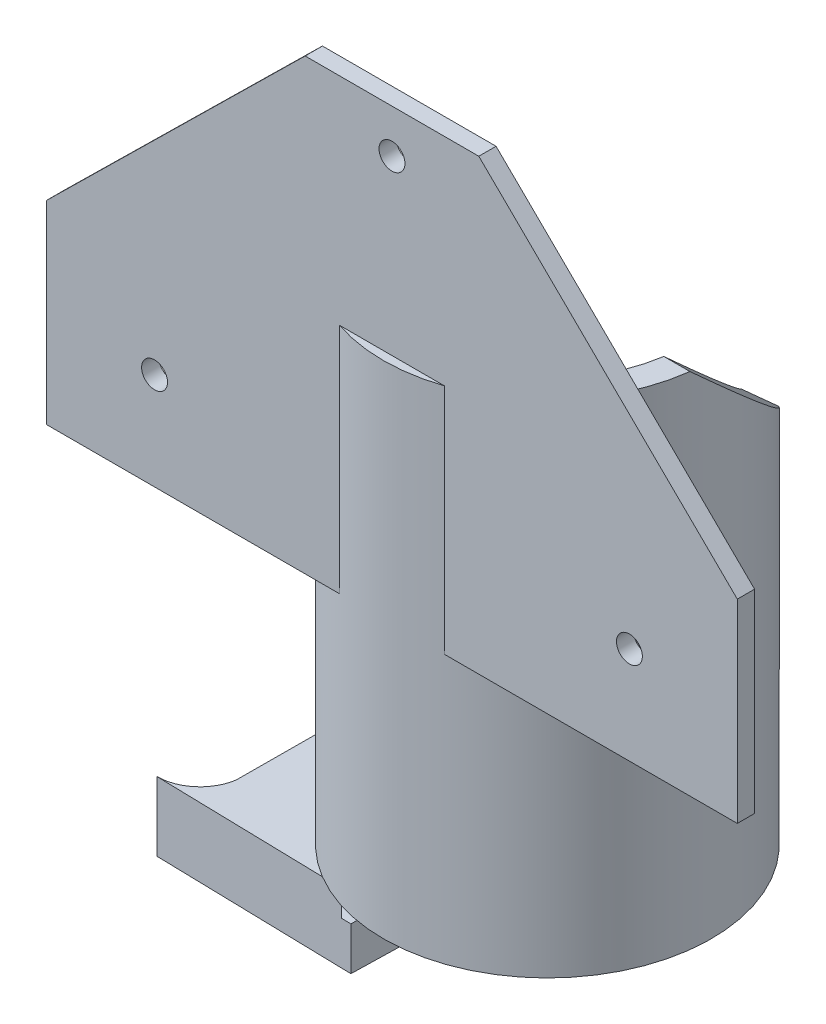
SolidWorks part; units mm, degrees
ref_plane "Front Plane" through (0, 0, 0) normal (0, 0, 1) x (1, 0, 0)
ref_plane "Top Plane" through (0, 0, 0) normal (0, 1, 0) x (1, 0, 0)
ref_plane "Right Plane" through (0, 0, 0) normal (1, 0, 0) x (0, 0, -1)
sketch "Sketch1" plane through (0, 0, 0) normal (0, 1, 0) x (1, 0, 0)
  circle A0 centre (0, 0) radius 19
  dimension "D1" = 38
extrude "Boss-Extrude1" add sketch "Sketch1" along normal blind 53 and the other way blind 5
sketch "Sketch2" plane through (0, 53, 0) normal (0, 1, 0) x (1, 0, 0)
  circle A0 centre (0, 0) radius 16
extrude "Cut-Extrude1" cut sketch "Sketch2" against normal blind 22
sketch "Sketch3" plane through (0, 53, 0) normal (0, 1, 0) x (1, 0, 0)
  line L1 (-12.5, 6) -> (12.5, 6)
  line L2 (-12.5, 6) -> (-12.5, 26)
  line L3 (-12.5, 26) -> (12.5, 26)
  line L4 (12.5, 6) -> (12.5, 26)
  line L5 (-12.5, 6) -> (12.5, 26) construction
  line L6 (-12.5, 26) -> (12.5, 6) construction
  circle A0 centre (0, 0) radius 16 construction
  point P0 (0, 16)
extrude "Cut-Extrude2" cut sketch "Sketch3" against normal blind 108
sketch "Sketch7" plane through (0, 0, 0) normal (1, 0, 0) x (0, 0, -1)
  line L0 (14.3091, 53) -> (14.3091, 38)
  line L1 (14.3091, -5) -> (14.3091, 53) construction
  line L2 (14.3091, 38) -> (-2.3455, 53)
  line L3 (14.3091, 53) -> (-19, 53) construction
  line L4 (-2.3455, 53) -> (14.3091, 53)
extrude "Cut-Extrude3" cut sketch "Sketch7" against normal blind 108 and the other way blind 108
ref_plane "Plane1" through (0, 0, 18) normal (0, 0, 1) x (1, 0, 0)
sketch "Sketch8" plane through (0, 0, 18) normal (0, 0, 1) x (1, 0, 0)
  line L1 (10.0571, 78.0232) -> (40, 48.5711)
  line L2 (40, 48.5711) -> (40, 26.0711)
  line L3 (40, 26.0711) -> (0, 26.0711)
  line L5 (0, -16.3611) -> (0, 16.3611) construction
  line L7 (-40, 26.0711) -> (0, 26.0711)
  line L8 (-40, 48.5711) -> (-40, 26.0711)
  line L9 (-10.0571, 78.0232) -> (-40, 48.5711)
  line L11 (-10.0571, 78.0232) -> (10.0571, 78.0232)
extrude "Boss-Extrude2" add sketch "Sketch8" against normal blind 2
sketch "Sketch10" plane through (0, 0, 16) normal (0, 0, -1) x (-1, 0, 0)
  line L0 (0, 53) -> (0, 73) construction
  line L1 (-19, 37.3211) -> (-27.5, 37.3211) construction
  line L2 (-19, 50.8876) -> (-19, -5) construction
  line L3 (19, 37.3211) -> (27.5, 37.3211) construction
  line L4 (19, -5) -> (19, 50.8876) construction
  circle A0 centre (-27.5, 37.3211) radius 1.5
  circle A1 centre (27.5, 37.3211) radius 1.5
  circle A2 centre (0, 73) radius 1.5
extrude "Cut-Extrude4" cut sketch "Sketch10" against normal blind 16
sketch "Sketch11" plane through (0, -5, 0) normal (0, -1, 0) x (1, 0, 0)
  line L11 (-6.3909, -8.8634) -> (-6.4802, -11.761)
  line L12 (-6.0124, 1.1829) -> (-6.3909, -8.8634)
  line L13 (-6.3756, 16.3864) -> (-6.0124, 1.1829)
  line L14 (-29.3909, 15.8366) -> (-6.3756, 16.3864)
  line L15 (-24.3909, -0.2751) -> (-24.4524, 11.6188)
  line L16 (-28.8909, -16.8634) -> (-31.8909, -16.8634)
  line L17 (-28.8909, -23.8634) -> (-28.8909, -16.8634)
  line L18 (-18.8909, -23.8634) -> (-28.8909, -23.8634)
  line L19 (-18.8909, -26.8634) -> (-18.8909, -23.8634)
  line L20 (-10.2759, -26.8054) -> (-18.8909, -26.8634)
  arc A5 (-6.4802, -11.761) -> (-8.7246, -13.0297) centre (-8.2368, -11.2731) cw
  arc A6 (-24.4524, 11.6188) -> (-29.3909, 15.8366) centre (-29.3908, 10.8366) ccw
  arc A7 (-31.8909, -16.8634) -> (-24.3909, -0.2751) centre (-9.7961, -16.8634) cw
  arc A8 (-9.9319, -25.1296) -> (-10.2759, -26.8054) centre (-10.9418, -25.7955) cw
  arc A9 (-9.9319, -25.1296) -> (-8.7246, -13.0297) centre (-6.3756, -19.3742) cw
extrude "Boss-Extrude3" add sketch "Sketch11" along normal blind 8
sketch "Sketch12" plane through (0, -13, 0) normal (0, -1, 0) x (1, 0, 0)
  line L17 (-31.8909, -26.8634) -> (-18.8909, -26.8634)
  line L18 (-31.8909, -16.8634) -> (-31.8909, -26.8634)
  line L19 (-28.8909, -16.8634) -> (-31.8909, -16.8634)
  line L20 (-28.8909, -23.8634) -> (-28.8909, -16.8634)
  line L21 (-18.8909, -23.8634) -> (-28.8909, -23.8634)
  line L22 (-18.8909, -26.8634) -> (-18.8909, -23.8634)
extrude "Boss-Extrude5" add sketch "Sketch12" along normal blind 18 and the other way blind 4 separate body
sketch "Sketch13" plane through (0, -31, 0) normal (0, -1, 0) x (1, 0, 0)
  line L7 (-44.3227, -26.8076) -> (-18.8227, -26.8076)
  line L8 (-44.3227, -16.8076) -> (-44.3227, -26.8076)
  line L9 (-28.8227, -16.8076) -> (-44.3227, -16.8076)
  line L10 (-28.8227, -23.8076) -> (-28.8227, -16.8076)
  line L11 (-18.8227, -23.8076) -> (-28.8227, -23.8076)
  line L12 (-18.8227, -26.8076) -> (-18.8227, -23.8076)
  circle A1 centre (-39.936, -19.6077) radius 1.5002
extrude "Boss-Extrude6" add sketch "Sketch13" along normal blind 8
sketch "Sketch15" plane through (0, 31, 0) normal (0, 1, 0) x (1, 0, 0)
  circle A0 centre (0, 0) radius 18
extrude "Cut-Extrude5" cut sketch "Sketch15" against normal blind 39
